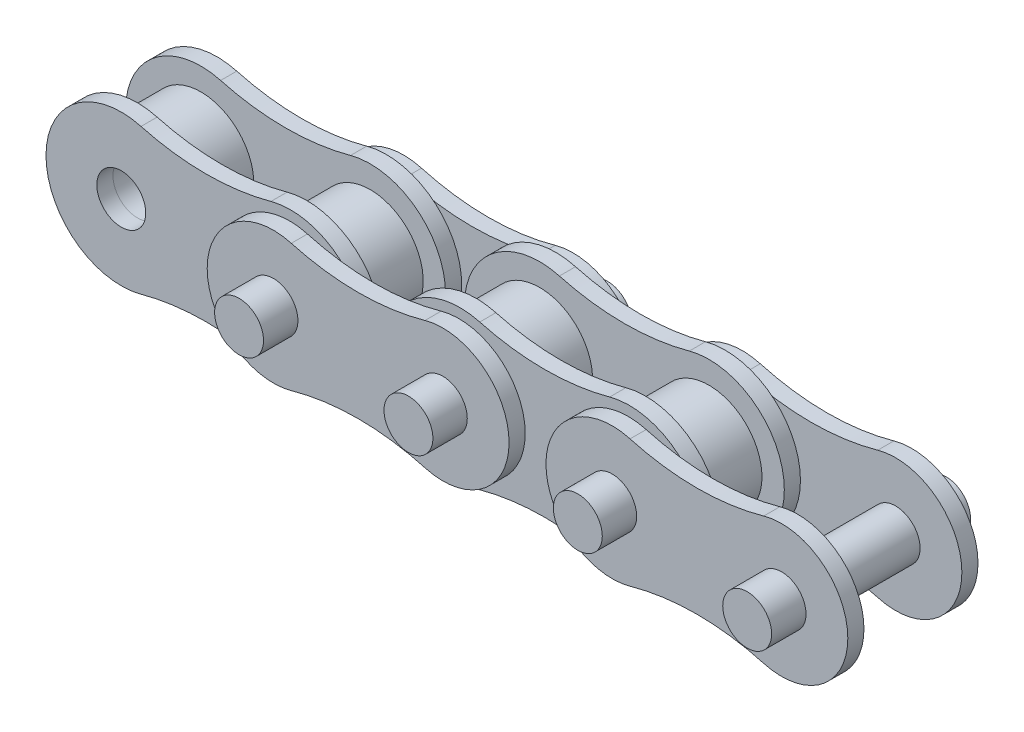
SolidWorks part; units mm, degrees
ref_plane "Front Plane" through (0, 0, 0) normal (0, 0, 1) x (1, 0, 0)
ref_plane "Top Plane" through (0, 0, 0) normal (0, 1, 0) x (1, 0, 0)
ref_plane "Right Plane" through (0, 0, 0) normal (1, 0, 0) x (0, 0, -1)
sketch "Sketch1" plane through (0, 0, 0) normal (0, 0, 1) x (1, 0, 0)
  line L0 (-4.0005, 0) -> (4.0005, 0) construction
  line L1 (-4.0005, 3.556) -> (-4.0005, -3.556) construction
  line L2 (0, -3.0226) -> (0, 3.0226) construction
  circle A0 centre (-4.0005, 0) radius 2.5
  circle A1 centre (4.0005, 0) radius 2.5
  circle A2 centre (-4.0005, 0) radius 1.1557
  circle A3 centre (4.0005, 0) radius 1.1557
  arc A4 (-3.0688, 3.4318) -> (-3.0688, -3.4318) centre (-4.0005, 0) ccw
  arc A5 (3.0688, -3.4318) -> (3.0688, 3.4318) centre (4.0005, 0) ccw
  arc A6 (-3.0688, 3.4318) -> (3.0688, 3.4318) centre (0, 14.7352) ccw
  arc A7 (-3.0688, -3.4318) -> (3.0688, -3.4318) centre (0, -14.7352) cw
  dimension "Roller Dia" = 5
  dimension "Pin Dia" = 2.3114
  dimension "Pitch" = 8.001
  dimension "H" = 7.112
  dimension "D2" = 6.0452
sketch "Sketch2" plane through (0, 0, 0) normal (0, 1, 0) x (1, 0, 0)
  line L0 (0, 1.5) -> (0, -1.5) construction
  point P2 (0, -2.262)
  point P4 (0, 2.262)
  point P5 (0, 2.3128)
  point P6 (0, 3.0748)
  dimension "W" = 3
  dimension "T" = 0.762
  dimension "D1" = 0.762
  dimension "T1" = 0.762
  dimension "D3" = 0.0508
ref_plane "Plane1" through (0, 0, 1.5) normal (0, 0, 1) x (1, 0, 0)
ref_plane "Plane2" through (0, 0, -2.3128) normal (0, 0, 1) x (1, 0, 0)
sketch "Sketch4" plane through (0, 0, 0) normal (0, 0, 1) x (1, 0, 0)
  circle A0 centre (-4.0005, 0) radius 2.5 construction
  circle A1 centre (-4.0005, 0) radius 2.5
  circle A2 centre (4.0005, 0) radius 2.5 construction
  circle A3 centre (4.0005, 0) radius 2.5
  circle A4 centre (-4.0005, 0) radius 1.1567
  circle A5 centre (4.0005, 0) radius 1.1567
  dimension "D1" = 2.3134
  dimension "D2" = 2.3134
extrude "Boss-Extrude1" add sketch "Sketch4" along normal mid plane 3
sketch "Sketch5" plane through (0, 0, 1.5) normal (0, 0, 1) x (1, 0, 0)
  arc A0 (-3.0688, 3.4318) -> (-3.0688, -3.4318) centre (-4.0005, 0) ccw construction
  arc A1 (-3.0688, 3.4318) -> (3.0688, 3.4318) centre (0, 14.7352) ccw construction
  circle A2 centre (-4.0005, 0) radius 1.1557 construction
  arc A3 (3.0688, -3.4318) -> (3.0688, 3.4318) centre (4.0005, 0) ccw construction
  circle A4 centre (4.0005, 0) radius 1.1557 construction
  arc A5 (3.0688, -3.4318) -> (-3.0688, -3.4318) centre (0, -14.7352) ccw construction
  arc A6 (-3.0688, 3.4318) -> (-3.0688, -3.4318) centre (-4.0005, 0) ccw
  arc A7 (-3.0688, 3.4318) -> (3.0688, 3.4318) centre (0, 14.7352) ccw
  circle A8 centre (-4.0005, 0) radius 1.1557
  arc A9 (3.0688, -3.4318) -> (3.0688, 3.4318) centre (4.0005, 0) ccw
  circle A10 centre (4.0005, 0) radius 1.1557
  arc A11 (3.0688, -3.4318) -> (-3.0688, -3.4318) centre (0, -14.7352) ccw
extrude "Boss-Extrude2" add sketch "Sketch5" along normal up to vertex (0.762 mm away) separate body up to point (0, 0, 2.262)
pattern_linear "LPattern1" count 2 spacing 8.001 along (1, 0, 0) of bodies 102
sketch "Sketch7" plane through (0, 0, -2.3128) normal (0, 0, 1) x (1, 0, 0)
  line L0 (12.0015, 3.1293) -> (12.0015, -3.1293) construction
  arc A0 (4.844, 3.0135) -> (4.844, -3.0135) centre (4.0005, 0) ccw
  arc A1 (11.158, -3.0135) -> (11.158, 3.0135) centre (12.0015, 0) ccw
  arc A2 (3.0688, -3.4318) -> (3.0688, 3.4318) centre (4.0005, 0) ccw construction
  circle A3 centre (12.0015, 0) radius 2.5 construction
  arc A4 (4.844, 3.0135) -> (11.158, 3.0135) centre (8.001, 14.2925) ccw
  arc A5 (4.844, -3.0135) -> (11.158, -3.0135) centre (8.001, -14.2925) cw
  arc A6 (-3.0688, 3.4318) -> (3.0688, 3.4318) centre (0, 14.7352) ccw construction
  circle A7 centre (4.0005, 0) radius 1.1557 construction
  circle A8 centre (4.0005, 0) radius 1.1557
  circle A9 centre (12.0015, 0) radius 1.1557
  dimension "D2" = 6.2586
extrude "Boss-Extrude3" add sketch "Sketch7" against normal up to vertex (0.762 mm away) separate body up to point (0, 0, -3.0748)
mirror "Mirror1" about plane through (0, 0, 0) normal (0, 0, 1) of bodies 103 105
sketch "Sketch8" plane through (0, 0, 0) normal (0, 0, 1) x (1, 0, 0)
  circle A0 centre (4.0005, 0) radius 1.1557
  circle A1 centre (12.0015, 0) radius 1.1557
  circle A2 centre (4.0005, 0) radius 1.1557 construction
  circle A3 centre (12.0015, 0) radius 1.1557 construction
extrude "Boss-Extrude4" add sketch "Sketch8" against normal blind 4.699 and the other way blind 4.699 separate body
pattern_linear "LPattern2" count 2 spacing 16.002 along (1, 0, 0) of bodies 109 108 107 106 105 104 103 102 101
delete or keep bodies "Body-Delete1" type delete bodies bodies 115
combine bodies "Combine1" operation type add bodies to combine 102 103 104 105 106 107 108 109 110 111 112 113 114 116 117 118 101
sketch "Sketch9" plane through (0, 0, 0) normal (0, 0, 1) x (1, 0, 0)
  line L0 (28.0035, 3.1293) -> (28.0035, -3.1293) construction
  line L1 (20.0025, 3.556) -> (20.0025, -3.556) construction
  arc A0 (19.0708, -3.4318) -> (19.0708, 3.4318) centre (20.0025, 0) ccw construction
  arc A1 (20.0025, -3.556) -> (20.0025, 3.556) centre (20.0025, 0) ccw
  arc A2 (27.16, -3.0135) -> (27.16, 3.0135) centre (28.0035, 0) ccw construction
  arc A3 (28.0035, -3.1293) -> (28.0035, 3.1293) centre (28.0035, 0) ccw
  circle A4 centre (-4.0005, 0) radius 2.5 construction
  circle A5 centre (-4.0005, 0) radius 2.5
equation "\"D2@Sketch1\" =\"H@Sketch1\"*.85"
equation "\"D1@Sketch2\" = \"T@Sketch2\""
equation "\"D1@Sketch4\" = \"Pin Dia@Sketch1\"+.002"
equation "\"D2@Sketch4\" = \"D1@Sketch4\""
equation "\"D1@Boss-Extrude1\" = \"W@Sketch2\""
equation "\"D3@LPattern1\" = \"Pitch@Sketch1\""
equation "\"D3@LPattern2\" = \"Pitch@Sketch1\"*2"
equation "\"D2@Sketch7\" = \"H@Sketch1\"*.88"
